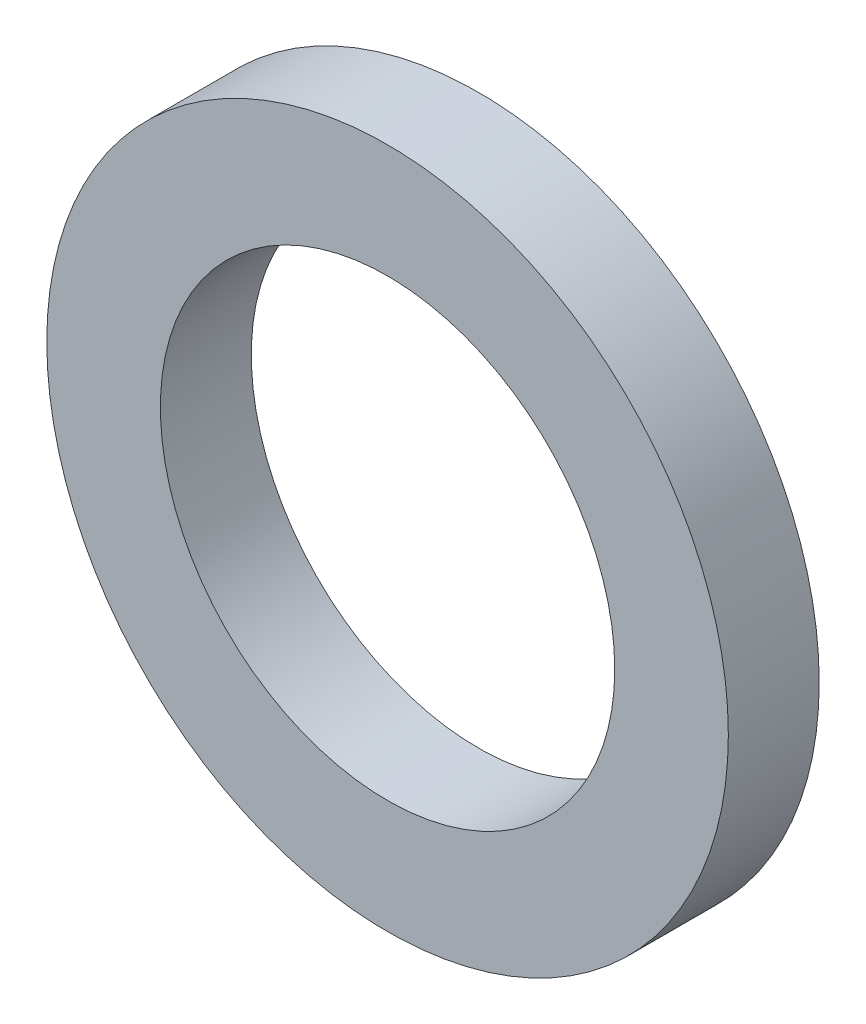
SolidWorks part; units mm, degrees
material "Alloy Steel (SS)"
ref_plane "Front Plane" through (0, 0, 0) normal (0, 0, 1) x (1, 0, 0)
ref_plane "Top Plane" through (0, 0, 0) normal (0, 1, 0) x (1, 0, 0)
ref_plane "Right Plane" through (0, 0, 0) normal (1, 0, 0) x (0, 0, -1)
sketch "Sketch1" plane through (0, 0, 0) normal (0, 0, 1) x (1, 0, 0)
  circle A0 centre (0, 0) radius 15
  circle A1 centre (0, 0) radius 10
  dimension "D1" = 30
  dimension "D2" = 20
extrude "Boss-Extrude1" add sketch "Sketch1" along normal blind 4
